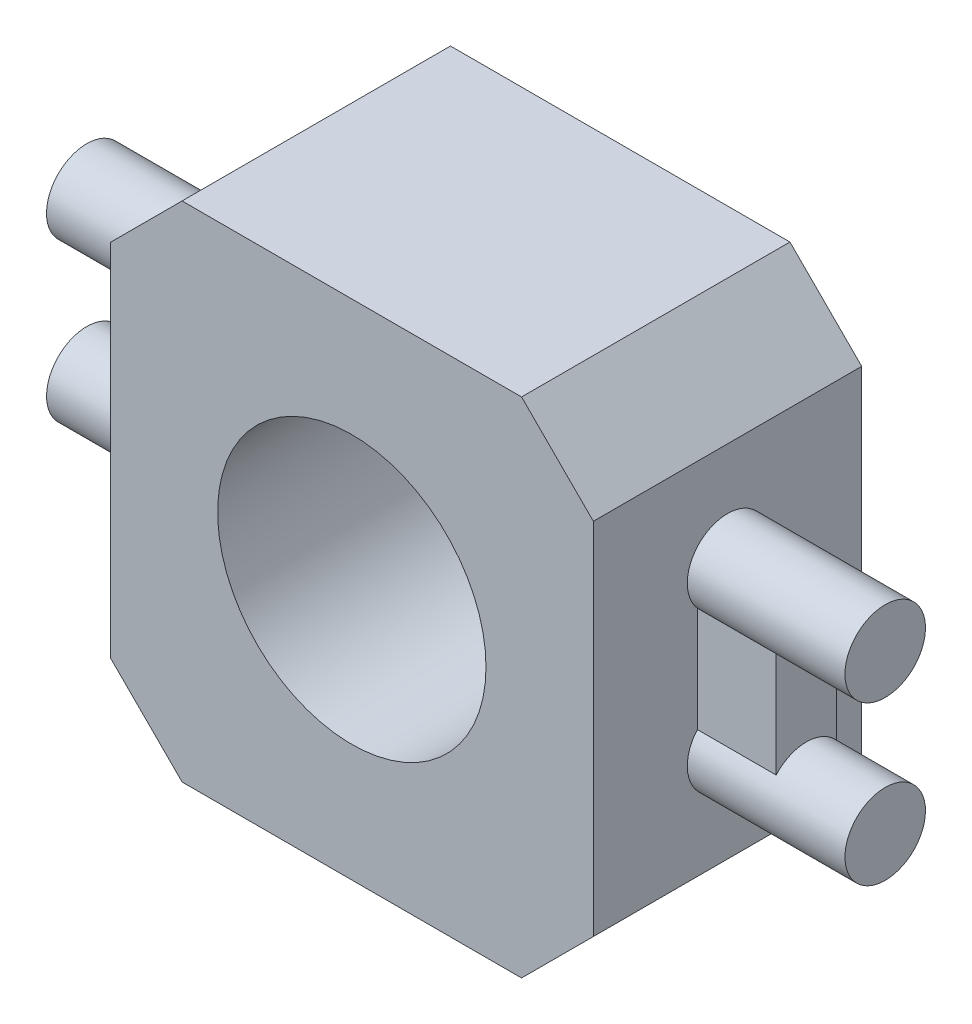
SolidWorks part; units mm, degrees
ref_plane "Front Plane" through (0, 0, 0) normal (0, 0, 1) x (1, 0, 0)
ref_plane "Top Plane" through (0, 0, 0) normal (0, 1, 0) x (1, 0, 0)
ref_plane "Right Plane" through (0, 0, 0) normal (1, 0, 0) x (0, 0, -1)
sketch "Sketch1" plane through (0, 0, 0) normal (0, 0, 1) x (1, 0, 0)
  line L0 (-2.53, 3.75) -> (-3.6, 2.68)
  line L1 (2.53, 3.75) -> (-2.53, 3.75)
  line L2 (3.6, 2.68) -> (3.6, -2.68)
  line L3 (2.53, -3.75) -> (-2.53, -3.75)
  line L4 (-3.6, 2.68) -> (-3.6, -2.68)
  line L5 (3.6, 3.75) -> (-3.6, -3.75) construction
  line L6 (3.6, -3.75) -> (-3.6, 3.75) construction
  line L7 (3.6, 2.68) -> (2.53, 3.75)
  line L8 (3.6, -2.68) -> (2.53, -3.75)
  line L9 (-2.53, -3.75) -> (-3.6, -2.68)
  point P0 (0, 0)
  dimension "D1" = 7.2
  dimension "D2" = 7.5
extrude "Boss-Extrude1" add sketch "Sketch1" along normal blind 4
sketch "Sketch2" plane through (0, 0, 4) normal (0, 0, 1) x (1, 0, 0)
  circle A0 centre (0, 0) radius 2
  dimension "D1" = 4
extrude "Cut-Extrude1" cut sketch "Sketch2" against normal through all
sketch "Sketch3" plane through (-3.6, 0, 0) normal (-1, 0, 0) x (0, 0, 1)
  line L0 (4, 2.68) -> (0, 2.68) construction
  line L1 (0, 2.68) -> (0, -2.68) construction
  line L2 (4, -2.68) -> (0, -2.68) construction
  circle A0 centre (2.0004, 1.18) radius 0.6
  circle A2 centre (2, -1.18) radius 0.6
  circle A3 centre (2.0004, 1.18) radius 0.6
  circle A4 centre (2, -1.18) radius 0.6
  dimension "D6" = 1.2
  dimension "D7" = 1.2
  dimension "D1" = 1.5
  dimension "D3" = 1.5
  dimension "D4" = 2
extrude "Boss-Extrude4" add sketch "Sketch3" along normal blind 2.35 contours A0 | A2
sketch "Sketch5" plane through (-3.6, 0, 0) normal (-1, 0, 0) x (0, 0, 1)
  line L0 (2.0004, 2.1268) -> (2.0004, -2.386) construction
  line L2 (2.4504, -1.3957) -> (1.5504, -1.3957)
  line L3 (2.4504, -1.3957) -> (2.4504, 1.1365)
  line L4 (2.4504, 1.1365) -> (1.5504, 1.1365)
  line L5 (1.5504, -1.3957) -> (1.5504, 1.1365)
  line L6 (2.4504, -1.3957) -> (1.5504, 1.1365) construction
  line L7 (2.4504, 1.1365) -> (1.5504, -1.3957) construction
  point P3 (2.0004, -0.1296)
  dimension "D1" = 0.9
extrude "Boss-Extrude5" add sketch "Sketch5" along normal blind 1.175 separate body
sketch "Sketch6" plane through (3.6, 0, 0) normal (1, 0, 0) x (0, 0, -1)
  line L0 (-4, -2.68) -> (0, -2.68) construction
  line L1 (-4, 2.68) -> (0, 2.68) construction
  line L2 (0, -2.68) -> (0, 2.68) construction
  line L3 (-4, -2.68) -> (-4, 2.68) construction
  circle A0 centre (-2, 1.18) radius 0.6
  circle A1 centre (-2, -1.18) radius 0.6
  dimension "D1" = 1.2
  dimension "D2" = 1.2
  dimension "D3" = 1.5
  dimension "D4" = 1.5
  dimension "D5" = 2
  dimension "D6" = 2
extrude "Boss-Extrude6" add sketch "Sketch6" along normal blind 2.35 contours A0 | A1
sketch "Sketch8" plane through (3.6, 0, 0) normal (1, 0, 0) x (0, 0, -1)
  line L1 (-2, 2.8246) -> (-2, -2.7449) construction
  line L3 (-2.45, -1.1631) -> (-1.55, -1.1631)
  line L4 (-2.45, -1.1631) -> (-2.45, 1.2428)
  line L5 (-2.45, 1.2428) -> (-1.55, 1.2428)
  line L6 (-1.55, -1.1631) -> (-1.55, 1.2428)
  line L7 (-2.45, -1.1631) -> (-1.55, 1.2428) construction
  line L8 (-2.45, 1.2428) -> (-1.55, -1.1631) construction
  point P7 (-2, 0.0399)
  dimension "D1" = 0.9
extrude "Boss-Extrude7" add sketch "Sketch8" along normal blind 1.175
